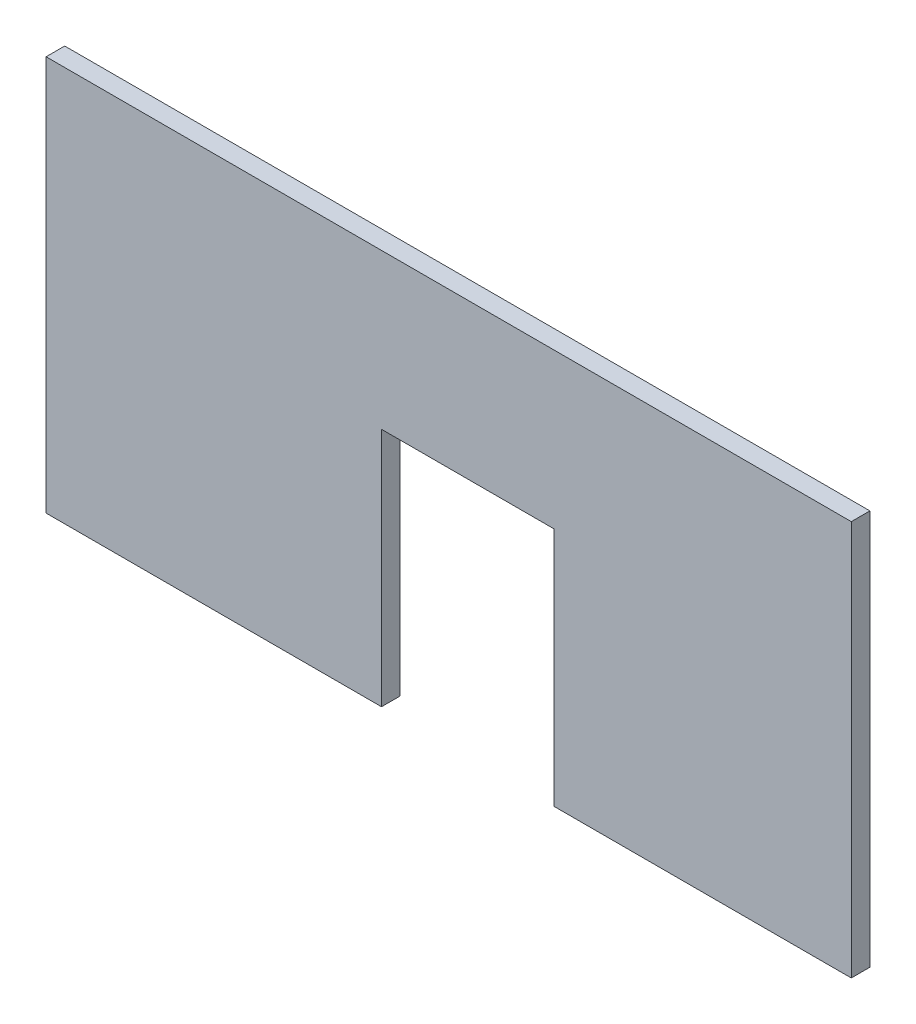
SolidWorks part; units mm, degrees
ref_plane "Front Plane" through (0, 0, 0) normal (0, 0, 1) x (1, 0, 0)
ref_plane "Top Plane" through (0, 0, 0) normal (0, 1, 0) x (1, 0, 0)
ref_plane "Right Plane" through (0, 0, 0) normal (1, 0, 0) x (0, 0, -1)
sketch "Sketch1" plane through (0, 0, 0) normal (0, 0, 1) x (1, 0, 0)
  line L0 (-35.7512, 1576.4855) -> (-35.7512, 1705.5429)
  line L1 (216.5353, 1576.4855) -> (56.9829, 1576.4855)
  line L2 (216.5353, 1576.4855) -> (216.5353, 1788.7384)
  line L3 (216.5353, 1788.7384) -> (-215.8753, 1788.7384)
  line L4 (-215.8753, 1576.4855) -> (-215.8753, 1788.7384)
  line L5 (-35.7512, 1705.5429) -> (56.9829, 1705.5429)
  line L6 (56.9829, 1705.5429) -> (56.9829, 1576.4855)
  line L7 (-0.7773, 1575.6376) -> (-0.7773, 1720.2473) construction
  line L8 (-35.7512, 1576.4855) -> (-215.8753, 1576.4855)
extrude "Boss-Extrude1" add sketch "Sketch1" along normal blind 10 from offset 48
